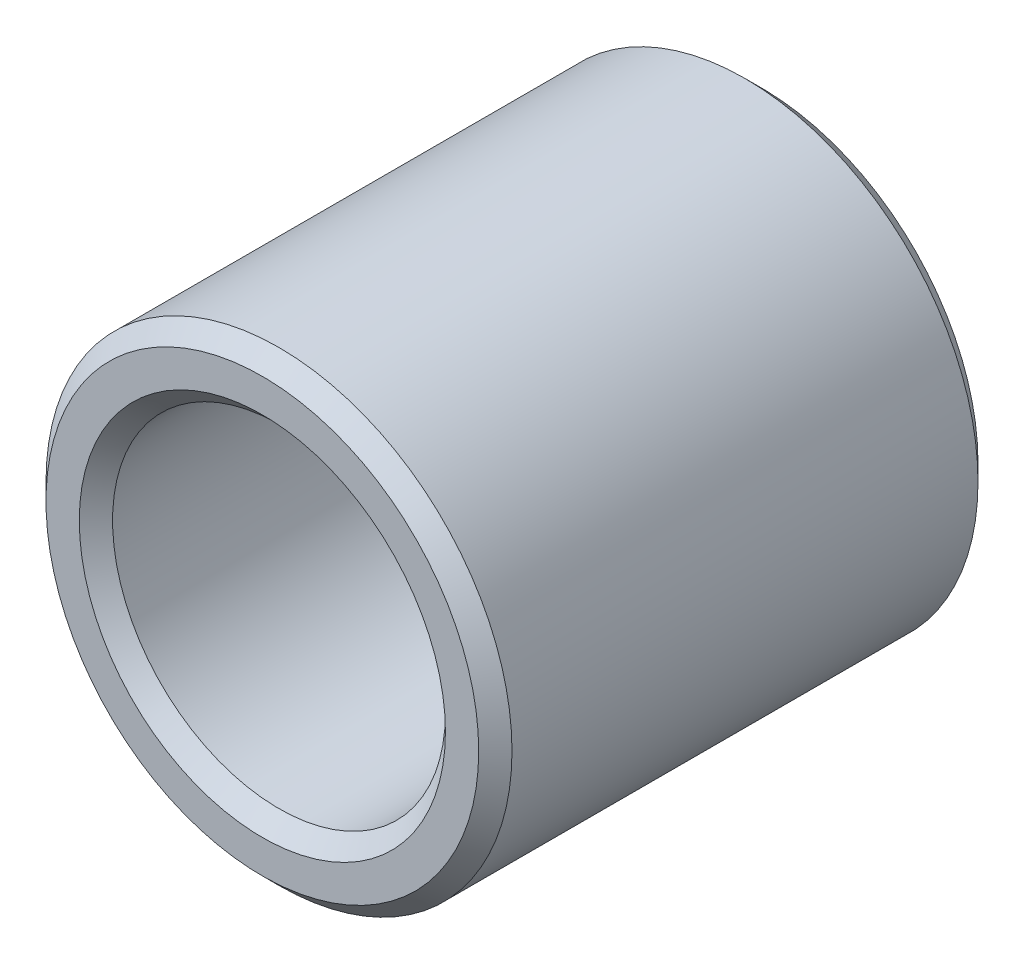
SolidWorks part; units mm, degrees
material "Литая легированная сталь"
ref_plane "Спереди" through (0, 0, 0) normal (0, 0, 1) x (1, 0, 0)
ref_plane "Сверху" through (0, 0, 0) normal (0, 1, 0) x (1, 0, 0)
ref_plane "Справа" through (0, 0, 0) normal (1, 0, 0) x (0, 0, -1)
other "Configuration Table"
sketch "Эскиз1" plane through (0, 0, 0) normal (0, 0, 1) x (1, 0, 0)
  circle A0 centre (0, 0) radius 5
  circle A1 centre (0, 0) radius 7
  dimension "D1" = 10
  dimension "D2" = 14
extrude "Бобышка-Вытянуть1" add sketch "Эскиз1" along normal blind 15
chamfer "Фаска1" distance 0.5 angle 45 4 edges at (5, 0, 0) (7, 0, 0) (5, 0, 15) (7, 0, 15)
